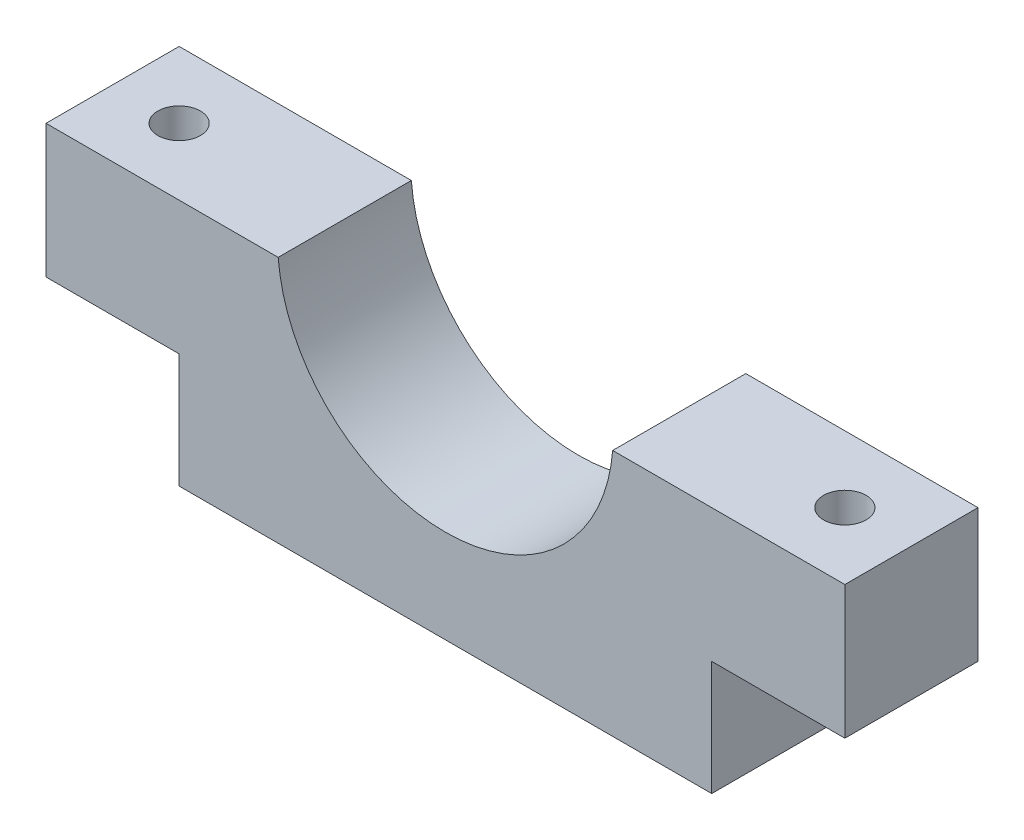
SolidWorks part; units mm, degrees
ref_plane "Спереди" through (0, 0, 0) normal (0, 0, 1) x (1, 0, 0)
ref_plane "Сверху" through (0, 0, 0) normal (0, 1, 0) x (1, 0, 0)
ref_plane "Справа" through (0, 0, 0) normal (1, 0, 0) x (0, 0, -1)
sketch "Эскиз1" plane through (0, 0, 0) normal (0, 0, 1) x (1, 0, 0)
  line L0 (12.5603, 9.3) -> (20, 9.3)
  line L1 (-20, -9.3) -> (20, -9.3)
  line L2 (-20, -9.3) -> (-20, 9.3)
  line L3 (-20, 9.3) -> (-12.5603, 9.3)
  line L4 (20, -9.3) -> (20, 9.3)
  line L5 (-20, -9.3) -> (20, 9.3) construction
  line L6 (-20, 9.3) -> (20, -9.3) construction
  line L7 (-20, 9.3) -> (-30, 9.3)
  line L8 (-20, 9.3) -> (-20, -0.7)
  line L9 (-20, -0.7) -> (-30, -0.7)
  line L10 (-30, 9.3) -> (-30, -0.7)
  line L11 (20, 9.3) -> (30, 9.3)
  line L12 (20, 9.3) -> (20, -0.7)
  line L13 (20, -0.7) -> (30, -0.7)
  line L14 (30, 9.3) -> (30, -0.7)
  arc A0 (-12.5603, 9.3) -> (12.5603, 9.3) centre (0, 10.3) ccw
  point P0 (0, 0)
  dimension "D3" = 25.2
  dimension "D1" = 40
  dimension "D2" = 18.6
  dimension "D4" = 1
  dimension "D5" = 10
  dimension "D6" = 10
extrude "Бобышка-Вытянуть1" add sketch "Эскиз1" along normal blind 10 contours L7 L10 L9 L2 | A0 L3 L2 L1 L4 L0 | L14 L11 L4 L13
sketch "Эскиз2" plane through (0, 9.3, 0) normal (0, 1, 0) x (1, 0, 0)
  line L0 (30, -10) -> (30, 0) construction
  line L1 (20, 0) -> (30, 0) construction
  line L2 (0, 0) -> (0, -10) construction
  line L3 (-12.5603, -10) -> (12.5603, -10) construction
  circle A0 centre (25, -5) radius 1.6
  circle A1 centre (-25, -5) radius 1.6
  point P4 (30, -5)
  point P7 (25, 0)
  dimension "D1" = 3.2
extrude "Вырез-Вытянуть1" cut sketch "Эскиз2" against normal blind 10
